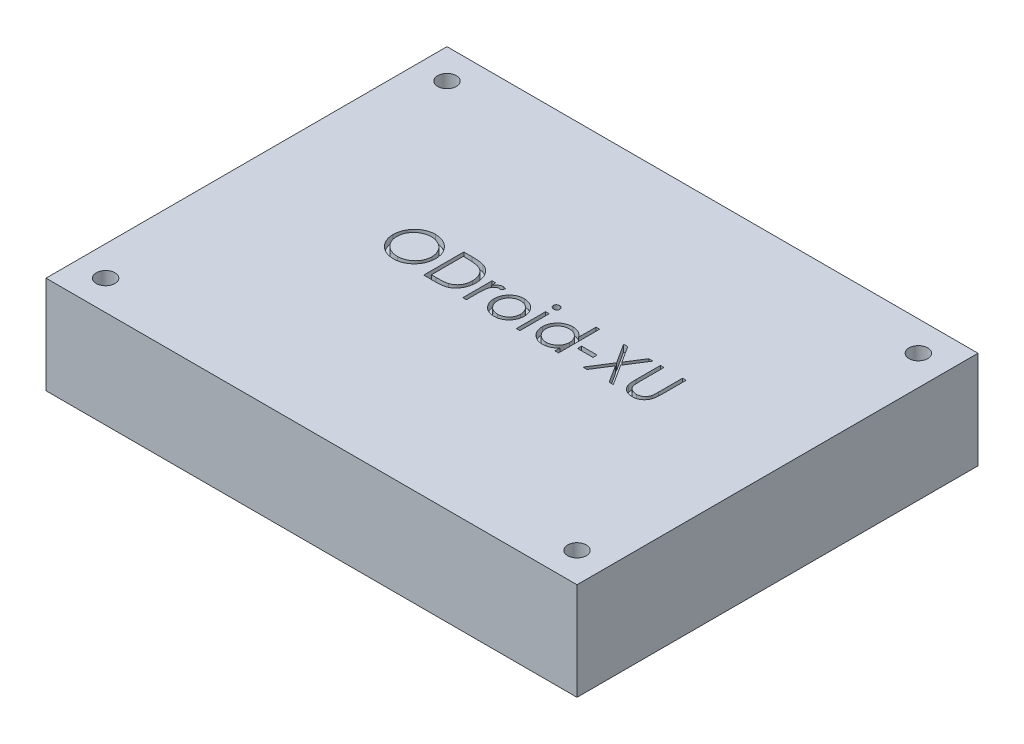
SolidWorks part; units mm, degrees
ref_plane "Front Plane" through (0, 0, 0) normal (0, 0, 1) x (1, 0, 0)
ref_plane "Top Plane" through (0, 0, 0) normal (0, 1, 0) x (1, 0, 0)
ref_plane "Right Plane" through (0, 0, 0) normal (1, 0, 0) x (0, 0, -1)
sketch "Sketch1" plane through (0, 0, 0) normal (0, 1, 0) x (1, 0, 0)
  line L1 (-49, -37) -> (49, -37)
  line L2 (-49, -37) -> (-49, 37)
  line L3 (-49, 37) -> (49, 37)
  line L4 (49, -37) -> (49, 37)
  line L5 (-49, -37) -> (49, 37) construction
  line L6 (-49, 37) -> (49, -37) construction
  point P0 (0, 0)
  dimension "D1" = 98
  dimension "D2" = 74
extrude "Boss-Extrude1" add sketch "Sketch1" along normal blind 18
sketch "Sketch2" plane through (0, 18, 0) normal (0, 1, 0) x (1, 0, 0)
  text T0 "ODroid-XU" font "Century Gothic" height in points 28
extrude "Cut-Extrude1" cut sketch "Sketch2" against normal blind 1.27
hole_wizard "#29 (0.136) Diameter Hole1" positions "Sketch4" profile "Sketch3" hole size "#29" standard "ANSI Inch" end condition through all
sketch "Sketch4" plane through (0, 18, 0) normal (0, 1, 0) x (1, 0, 0)
  line L0 (-43.5, -31.5) -> (-43.5, -37) construction
  line L1 (-49, -37) -> (49, -37) construction
  line L4 (-43.5, 31.5) -> (-43.5, 37) construction
  line L5 (49, 37) -> (-49, 37) construction
  line L7 (-49, -31.5) -> (-43.5, -31.5) construction
  line L8 (-49, 37) -> (-49, -37) construction
  line L11 (43.5, -31.5) -> (49, -31.5) construction
  line L12 (49, -37) -> (49, 37) construction
  point P0 (-43.5, 31.5)
  point P2 (43.5, 31.5)
  point P4 (43.5, -31.5)
  point P6 (-43.5, -31.5)
  dimension "D1" = 63
  dimension "D2" = 87
sketch "Sketch3" plane through (-43.5, 18, -31.5) normal (1, 0, 0) x (0, 0, 1)
  line L0 (0, 0) -> (0, 18)
  line L1 (0, 18) -> (1.7272, 18)
  line L2 (1.7272, 18) -> (1.7272, 0)
  line L5 (1.7272, 0) -> (0, 0)
  line L11 (0, -6.35) -> (0, 107.95) construction
  dimension "Thru Hole Dia." = 3.4544
  dimension "Thru Hole Depth" = 18
